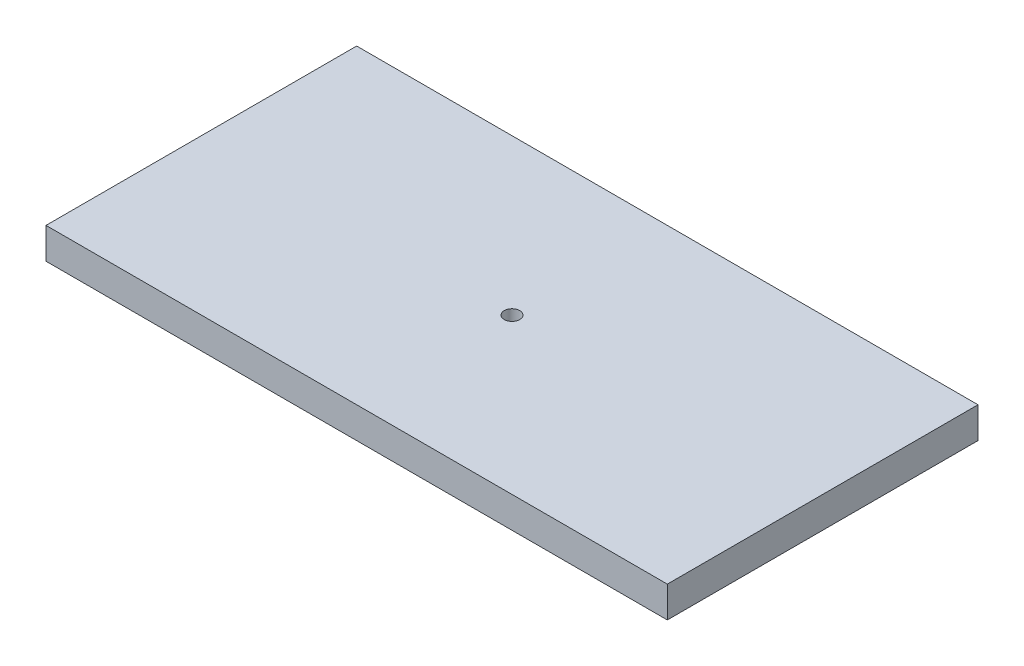
SolidWorks part; units mm, degrees
ref_plane "Front Plane" through (0, 0, 0) normal (0, 0, 1) x (1, 0, 0)
ref_plane "Top Plane" through (0, 0, 0) normal (0, 1, 0) x (1, 0, 0)
ref_plane "Right Plane" through (0, 0, 0) normal (1, 0, 0) x (0, 0, -1)
sketch "Sketch1" plane through (0, 0, 0) normal (0, 1, 0) x (1, 0, 0)
  line L1 (0, 0) -> (200, 0)
  line L2 (0, 0) -> (0, 100)
  line L3 (0, 100) -> (200, 100)
  line L4 (200, 0) -> (200, 100)
  dimension "D1" = 200
  dimension "D2" = 100
extrude "Boss-Extrude1" add sketch "Sketch1" along normal blind 10
sketch "Sketch2" plane through (0, 10, 0) normal (0, 1, 0) x (1, 0, 0)
  circle A0 centre (100, 50) radius 2.5
  dimension "D1" = 5
extrude "Cut-Extrude1" cut sketch "Sketch2" against normal blind 5
